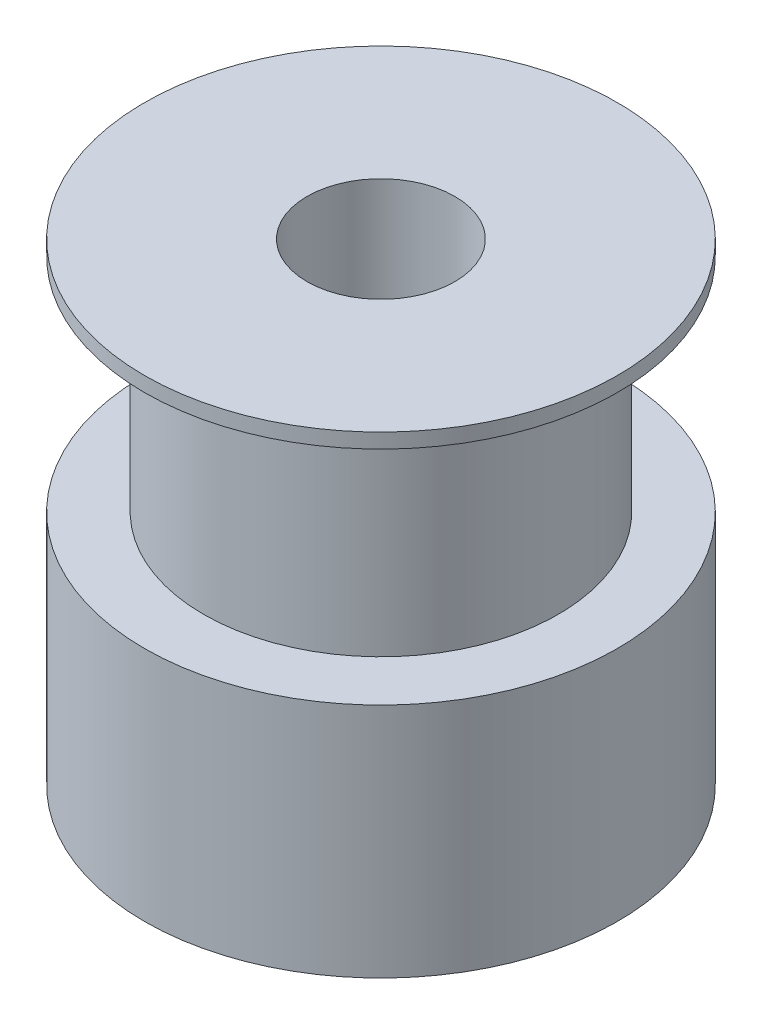
SolidWorks part; units mm, degrees
ref_plane "前视基准面" through (0, 0, 0) normal (0, 0, 1) x (1, 0, 0)
ref_plane "上视基准面" through (0, 0, 0) normal (0, 1, 0) x (1, 0, 0)
ref_plane "右视基准面" through (0, 0, 0) normal (1, 0, 0) x (0, 0, -1)
sketch "草图1" plane through (0, 0, 0) normal (0, 1, 0) x (1, 0, 0)
  circle A0 centre (0, 0) radius 8
  dimension "D1" = 16
extrude "凸台-拉伸1" add sketch "草图1" along normal blind 8
sketch "草图2" plane through (0, 8, 0) normal (0, 1, 0) x (1, 0, 0)
  circle A0 centre (0, 0) radius 6
  dimension "D1" = 12
extrude "凸台-拉伸2" add sketch "草图2" along normal blind 7.5
sketch "草图3" plane through (0, 15.5, 0) normal (0, 1, 0) x (1, 0, 0)
  circle A0 centre (0, 0) radius 8
  dimension "D1" = 16
extrude "凸台-拉伸3" add sketch "草图3" along normal blind 0.5
sketch "草图4" plane through (0, 0, 0) normal (0, -1, 0) x (1, 0, 0)
  circle A0 centre (0, 0) radius 2.5
  dimension "D1" = 5
extrude "切除-拉伸1" cut sketch "草图4" against normal up to next
